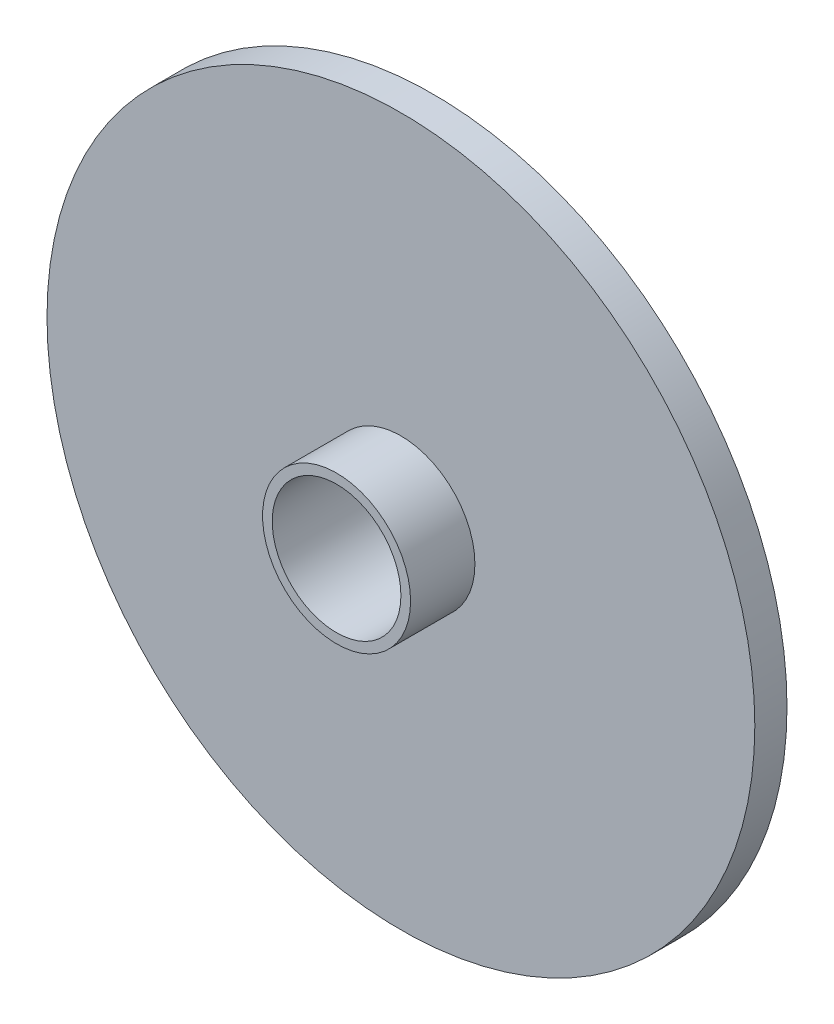
SolidWorks part; units mm, degrees
ref_plane "Ön Düzlem" through (0, 0, 0) normal (0, 0, 1) x (1, 0, 0)
ref_plane "Üst Düzlem" through (0, 0, 0) normal (0, 1, 0) x (1, 0, 0)
ref_plane "Sağ Düzlem" through (0, 0, 0) normal (1, 0, 0) x (0, 0, -1)
sketch "Sketch1" plane through (0, 0, 0) normal (0, 0, 1) x (1, 0, 0)
  circle A0 centre (0, 0) radius 55
  dimension "D1" = 110
extrude "Boss-Extrude1" add sketch "Sketch1" along normal blind 5
sketch "Sketch2" plane through (0, 0, 5) normal (0, 0, 1) x (1, 0, 0)
  circle A0 centre (0, 0) radius 10
  circle A1 centre (0, 0) radius 11.5
  dimension "D1" = 20
  dimension "D2" = 23
extrude "Boss-Extrude2" add sketch "Sketch2" along normal blind 10
sketch "Sketch3" plane through (0, 0, 5) normal (0, 0, 1) x (1, 0, 0)
  circle A0 centre (0, 0) radius 10
extrude "Cut-Extrude1" cut sketch "Sketch3" against normal through all
